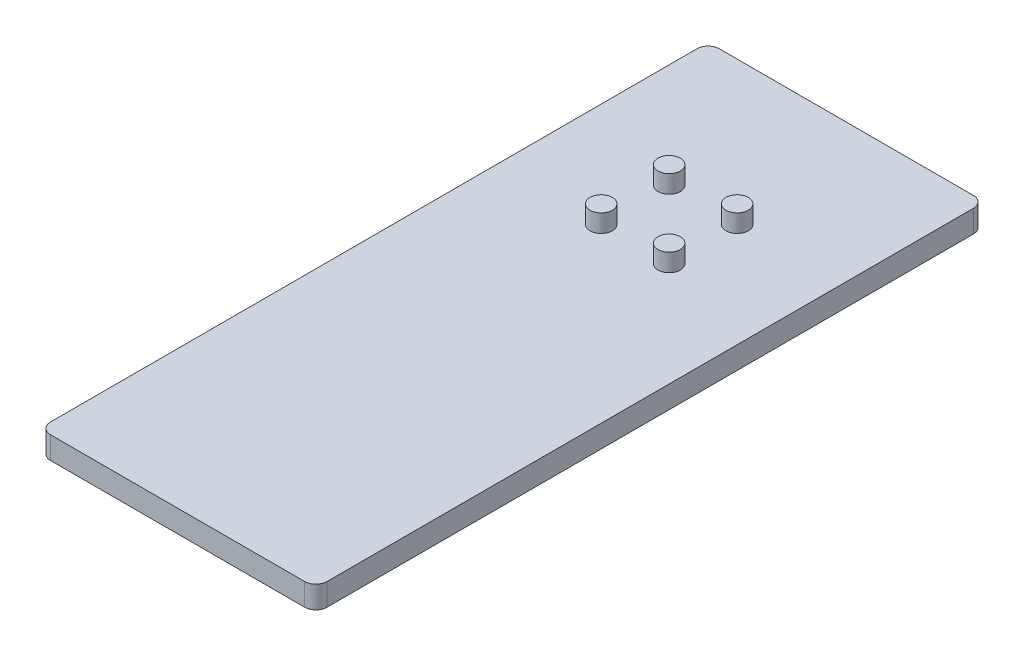
SolidWorks part; units mm, degrees
ref_plane "Front Plane" through (0, 0, 0) normal (0, 0, 1) x (1, 0, 0)
ref_plane "Top Plane" through (0, 0, 0) normal (0, 1, 0) x (1, 0, 0)
ref_plane "Right Plane" through (0, 0, 0) normal (1, 0, 0) x (0, 0, -1)
sketch "Sketch1" plane through (0, 0, 0) normal (0, 1, 0) x (1, 0, 0)
  line L1 (-31, 75) -> (31, 75)
  line L2 (-31, 75) -> (-31, -75)
  line L3 (-31, -75) -> (31, -75)
  line L4 (31, 75) -> (31, -75)
  line L5 (-31, 75) -> (31, -75) construction
  line L6 (-31, -75) -> (31, 75) construction
  point P0 (0, 0)
  dimension "D1" = 150
  dimension "D2" = 62
extrude "Boss-Extrude1" add sketch "Sketch1" along normal blind 5
fillet "Fillet1" radius 2.5 4 edges at (-31, 2.5, -75) (31, 2.5, -75) (31, 2.5, 75) (-31, 2.5, 75)
sketch "Sketch2" plane through (0, 5, 0) normal (0, 1, 0) x (1, 0, 0)
  line L0 (-15.25, 50.5) -> (-15.25, 20)
  line L1 (15.25, 50.5) -> (15.25, 20)
  line L2 (12.5, -45) -> (-12.5, -45)
  line L3 (12.5, -45) -> (12.5, -20)
  line L4 (12.5, -20) -> (-12.5, -20)
  line L5 (-12.5, -45) -> (-12.5, -20)
  line L6 (12.5, -45) -> (-12.5, -20) construction
  line L7 (12.5, -20) -> (-12.5, -45) construction
  line L8 (-15.25, 50.5) -> (15.25, 50.5)
  line L10 (-15.25, 20) -> (15.25, 20)
  point P0 (0, -32.5)
  point P1 (0, 20)
  point P8 (0, -20)
  dimension "D1" = 25
  dimension "D2" = 25
  dimension "D3" = 30.5
  dimension "D4" = 30.5
  dimension "D5" = 20
  dimension "D6" = 20
sketch "Sketch3" plane through (0, 5, 0) normal (0, 1, 0) x (1, 0, 0)
  circle A0 centre (-7.625, 42.875) radius 2.5
  circle A1 centre (7.625, 42.875) radius 2.5
  circle A2 centre (7.625, 27.625) radius 2.5
  circle A3 centre (-7.625, 27.625) radius 2.5
extrude "Boss-Extrude2" add sketch "Sketch3" along normal blind 4
